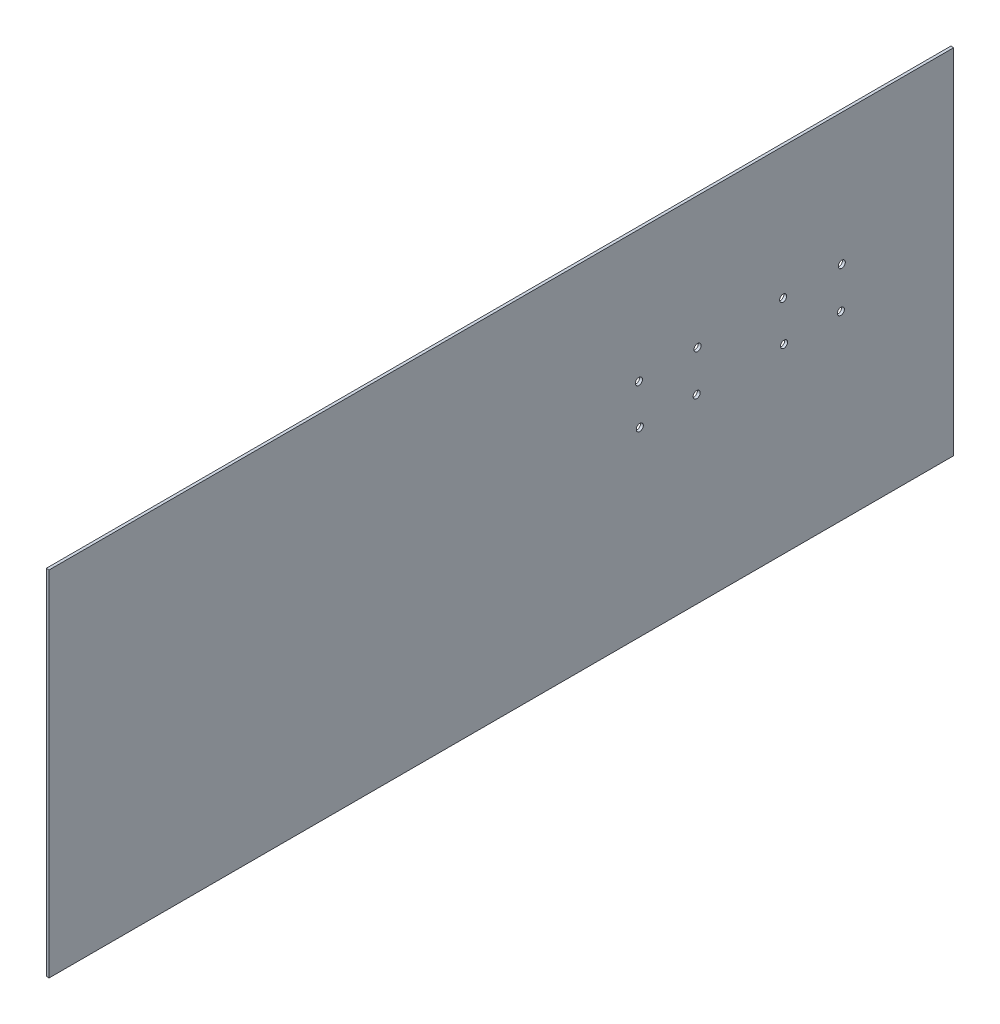
SolidWorks part; units mm, degrees
ref_plane "Front Plane" through (0, 0, 0) normal (0, 0, 1) x (1, 0, 0)
ref_plane "Top Plane" through (0, 0, 0) normal (0, 1, 0) x (1, 0, 0)
ref_plane "Right Plane" through (0, 0, 0) normal (1, 0, 0) x (0, 0, -1)
sketch "Sketch1" plane through (0, 0, 0) normal (1, 0, 0) x (0, 0, -1)
  line L0 (1.2451, 135.7198) -> (1.2451, -114.2802) construction
  line L1 (-318.7549, 135.7198) -> (321.2451, 135.7198)
  line L2 (-318.7549, 135.7198) -> (-318.7549, -114.2802)
  line L3 (-318.7549, -114.2802) -> (321.2451, -114.2802)
  line L4 (321.2451, 135.7198) -> (321.2451, -114.2802)
  line L5 (-158.7549, 10.7198) -> (161.2451, 10.7198) construction
  line L6 (-158.7549, 10.7198) -> (-158.7549, 135.7198) construction
  line L8 (161.2451, 10.7198) -> (161.2451, 135.7198) construction
  circle A0 centre (98.5187, 42.6102) radius 2.5
  circle A1 centre (140.0098, 42.6102) radius 2.5
  circle A2 centre (99.1463, 14.0702) radius 2.5
  circle A3 centre (139.3629, 14.0702) radius 2.5
  circle A4 centre (200.5458, 42.6102) radius 2.5
  circle A5 centre (201.1733, 14.0702) radius 2.5
  circle A6 centre (241.3899, 14.0702) radius 2.5
  circle A7 centre (242.0368, 42.6102) radius 2.5
  circle A8 centre (-158.7549, 10.7198) radius 28.0033 construction
  circle A9 centre (161.2451, 10.7198) radius 25.1308 construction
  dimension "D1" = 640
  dimension "D2" = 250
extrude "Boss-Extrude1" add sketch "Sketch1" along normal blind 2
